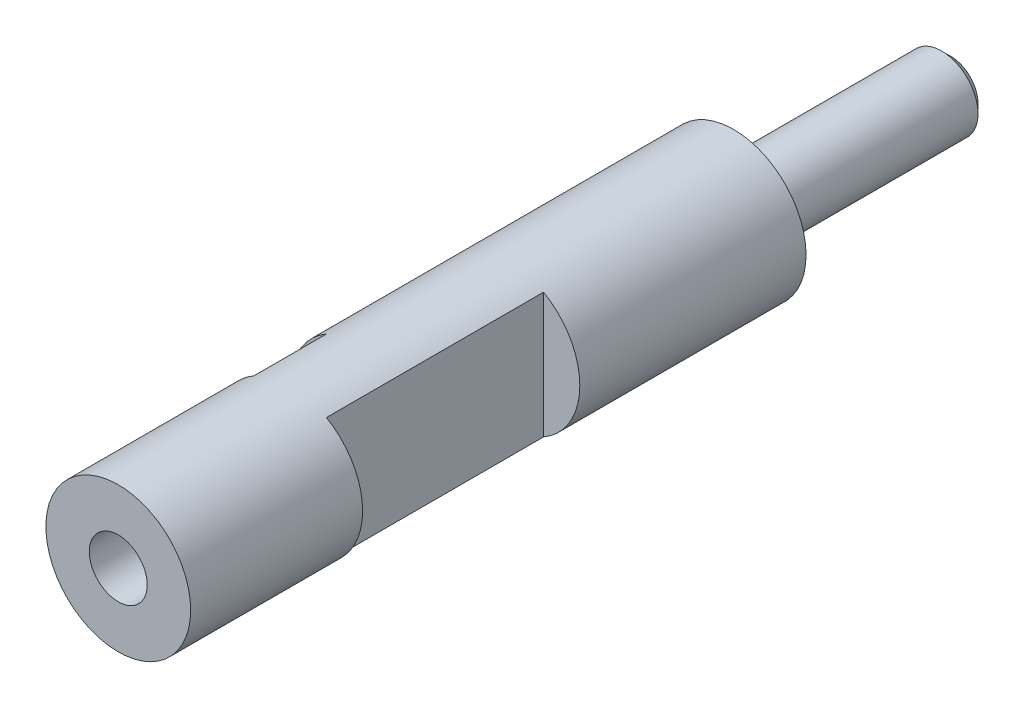
SolidWorks part; units mm, degrees
ref_plane "Front Plane" through (0, 0, 0) normal (0, 0, 1) x (1, 0, 0)
ref_plane "Top Plane" through (0, 0, 0) normal (0, 1, 0) x (1, 0, 0)
ref_plane "Right Plane" through (0, 0, 0) normal (1, 0, 0) x (0, 0, -1)
sketch "Sketch1" plane through (0, 0, 0) normal (0, 0, 1) x (1, 0, 0)
  circle A0 centre (0, 0) radius 2
  dimension "D1" = 4
extrude "Boss-Extrude1" add sketch "Sketch1" along normal blind 12
chamfer "Chamfer1" distance 0.5 angle 45 1 edges at (2, 0, 0)
sketch "Sketch2" plane through (0, 0, 12) normal (0, 0, 1) x (1, 0, 0)
  circle A0 centre (0, 0) radius 4
  dimension "D1" = 8
extrude "Boss-Extrude2" add sketch "Sketch2" along normal blind 34
sketch "Sketch3" plane through (0, 0, 46) normal (0, 0, 1) x (1, 0, 0)
  circle A0 centre (0, 0) radius 1.6
  dimension "D1" = 3.2
extrude "Cut-Extrude1" cut sketch "Sketch3" against normal blind 14
sketch "Sketch4" plane through (0, 0, 0) normal (0, 1, 0) x (1, 0, 0)
  line L0 (4, -46) -> (4, -12) construction
  line L1 (4, -24.5) -> (2, -24.5)
  line L2 (4, -24.5) -> (4, -36.5)
  line L3 (4, -36.5) -> (2, -36.5)
  line L4 (2, -24.5) -> (2, -36.5)
  line L5 (-4, -46) -> (4, -46) construction
  dimension "D1" = 12
  dimension "D2" = 9.5
  dimension "D3" = 2
extrude "Cut-Extrude2" cut sketch "Sketch4" against normal through all both and the other way through all
hole_wizard "M3x0.5 Tapped Hole1" positions "3DSketch1" profile "Sketch5" tap size "M3x0.5" standard "ANSI Metric"
sketch3d "3DSketch1"
  line L0 (0, 0, 46) -> (0, 0, 12) construction
  point P0 (0, 0, 46)
sketch "Sketch5" plane through (0, 0, 46) normal (1, 0, 0) x (0, -1, 0)
  line L0 (0, 0) -> (0, 14)
  line L1 (0, 14) -> (1.25, 13.2489)
  line L2 (1.25, 13.2489) -> (1.25, 0.275)
  line L3 (1.25, 0.275) -> (1.525, 0)
  line L5 (1.525, 0) -> (0, 0)
  line L6 (-1.25, 0.275) -> (-1.525, 0) construction
  line L10 (0, 14) -> (-1.25, 13.2489) construction
  line L11 (0, -6.35) -> (0, 107.95) construction
  dimension "Tap Drill Dia." = 2.5
  dimension "Tap Drill Depth" = 14
  dimension "Near C'Sink Dia." = 3.05
  dimension "Near C'Sink Angle" = 90
  dimension "Drill Angle" = 118
sketch "Sketch7" plane through (0, 0, 0) normal (0, 1, 0) x (1, 0, 0)
  line L0 (-4, -12) -> (-4, -46) construction
  line L1 (-4, -32.5) -> (-2, -32.5)
  line L2 (-4, -32.5) -> (-4, -36.5)
  line L3 (-4, -36.5) -> (-2, -36.5)
  line L4 (-2, -32.5) -> (-2, -36.5)
  line L5 (-4, -34.5) -> (2, -34.5) construction
  line L6 (2, -36.5) -> (2, -24.5) construction
  line L7 (-4, -46) -> (4, -46) construction
  dimension "D1" = 11.5
  dimension "D2" = 4
  dimension "D3" = 2
extrude "Cut-Extrude3" cut sketch "Sketch7" against normal through all both and the other way through all
hole_wizard "M3x0.5 Tapped Hole3" positions "3DSketch4" profile "Sketch10" tap size "M3x0.5" standard "ANSI Metric"
sketch3d "3DSketch4"
  point P0 (-2, -0.0157, 34.5784)
sketch "Sketch10" plane through (-2, -0.0157, 34.5784) normal (0, 1, 0) x (0, 0, 1)
  line L0 (0, 0) -> (0, 2)
  line L1 (0, 2) -> (1.25, 1.2489)
  line L2 (1.25, 1.2489) -> (1.25, 0.275)
  line L3 (1.25, 0.275) -> (1.525, 0)
  line L5 (1.525, 0) -> (0, 0)
  line L6 (-1.25, 0.275) -> (-1.525, 0) construction
  line L10 (0, 2) -> (-1.25, 1.2489) construction
  line L11 (0, -6.35) -> (0, 107.95) construction
  dimension "Tap Drill Dia." = 2.5
  dimension "Tap Drill Depth" = 2
  dimension "Near C'Sink Dia." = 3.05
  dimension "Near C'Sink Angle" = 90
  dimension "Drill Angle" = 118
cosmetic thread "Hole Thread1" parameters "D1"=6, "D2"=3
